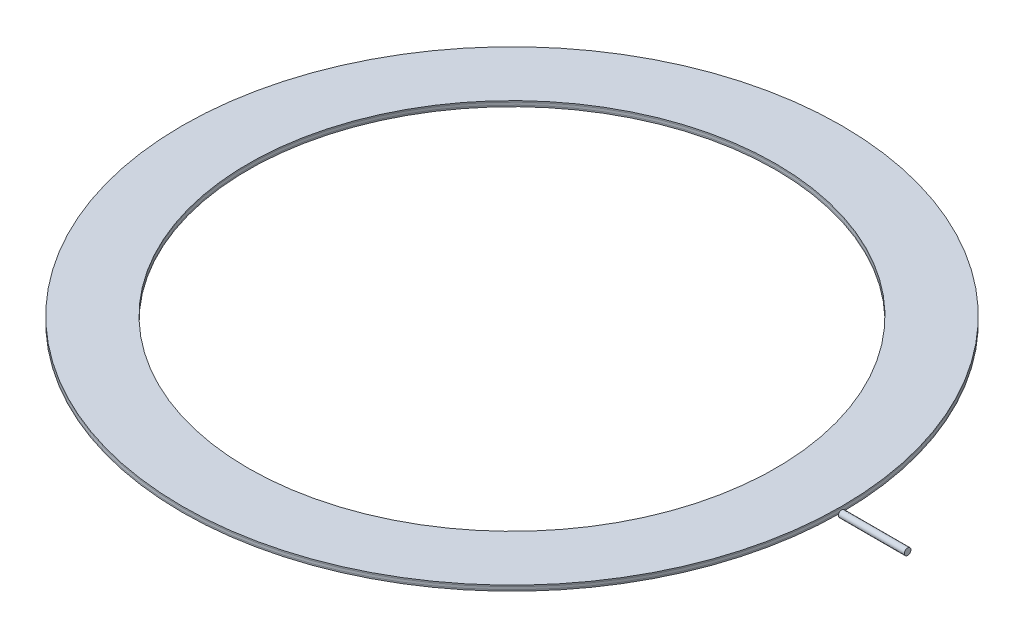
SolidWorks part; units mm, degrees
material "1060 Alloy"
ref_plane "Front Plane" through (0, 0, 0) normal (0, 0, 1) x (1, 0, 0)
ref_plane "Top Plane" through (0, 0, 0) normal (0, 1, 0) x (1, 0, 0)
ref_plane "Right Plane" through (0, 0, 0) normal (1, 0, 0) x (0, 0, -1)
sketch "Sketch1" plane through (0, 0, 0) normal (0, 1, 0) x (1, 0, 0)
  circle A0 centre (0, 0) radius 20
  circle A1 centre (0, 0) radius 25
  dimension "D1" = 50
  dimension "D2" = 5
extrude "Boss-Extrude1" add sketch "Sketch1" along normal blind 0.1
sketch "Sketch2" plane through (0, 0, 0) normal (0, 0, 1) x (1, 0, 0)
  line L0 (0, 0) -> (50000, 0) construction
  line L1 (0, 0) -> (0, -50000) construction
  line L2 (25, 0.1) -> (25, 50000.1) construction
  line L3 (20, 0.7447) -> (20, 50000.7447) construction
  line L4 (20, 0.815) -> (25, 0.815) construction
  line L5 (22.5, 0.815) -> (22.5, 50000.815) construction
  line L6 (22.5, -0.08) -> (25, -0.08)
  point P14 (22.5, 0.815)
  dimension "D1" = 5
  dimension "D2" = 0.08
sweep "Sweep1" add path "Sketch2" circular profile diameter 0.16 parameters "D3"=0.16
sketch "Sketch11" plane through (0, 0, 0) normal (0, 0, 1) x (1, 0, 0)
  line L0 (25, -0.08) -> (30, -0.08)
  dimension "D1" = 5
sweep "Sweep2" add path "Sketch11" circular profile diameter 0.5 parameters "D3"=0.5
sketch "Sketch18" plane through (0, 0.1, 0) normal (0, 1, 0) x (1, 0, 0)
  circle A0 centre (0, 0) radius 25
  circle A1 centre (0, 0) radius 20
  circle A2 centre (0, 0) radius 25 construction
  circle A3 centre (0, 0) radius 20 construction
extrude "Boss-Extrude2" add sketch "Sketch18" along normal blind 0.2 separate body
sketch "Sketch19" plane through (0, 0.3, 0) normal (0, 1, 0) x (1, 0, 0)
  circle A0 centre (0, 0) radius 25
  circle A1 centre (0, 0) radius 20
  circle A2 centre (0, 0) radius 25 construction
  circle A3 centre (0, 0) radius 20 construction
extrude "Boss-Extrude3" add sketch "Sketch19" along normal blind 0.1 separate body
